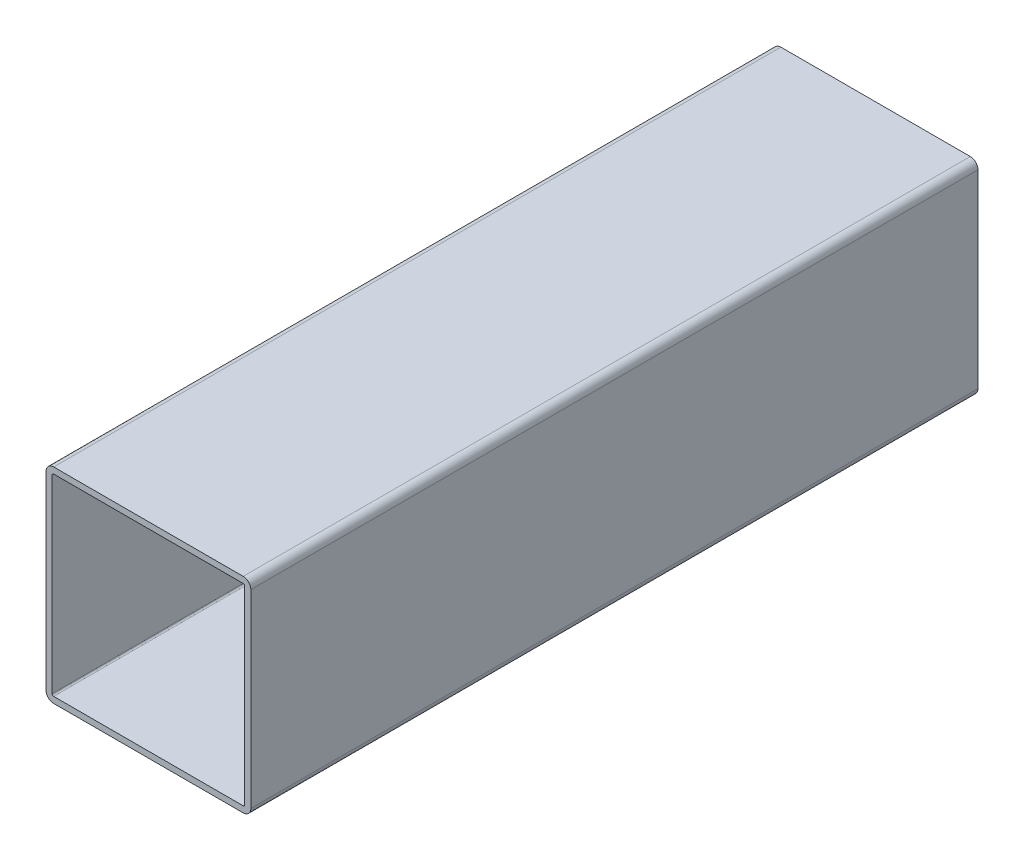
SolidWorks part; units mm, degrees
material "AISI 1020 Steel, Cold Rolled"
ref_plane "Front Plane" through (0, 0, 0) normal (0, 0, 1) x (1, 0, 0)
ref_plane "Top Plane" through (0, 0, 0) normal (0, 1, 0) x (1, 0, 0)
ref_plane "Right Plane" through (0, 0, 0) normal (1, 0, 0) x (0, 0, -1)
sketch "Sketch1" plane through (0, 0, 0) normal (0, 1, 0) x (1, 0, 0)
  line L0 (0, 0) -> (0, 142)
  dimension "D1" = 142
other "Structural Member1"
ref_plane "Plane1" through (0, 0, 0) normal (0, 0, -1) x (-1, 0, 0)
sketch "Sketch12" plane through (0, 0, 0) normal (0, 0, -1) x (-1, 0, 0)
  line L0 (-18.5, -18.8) -> (18.5, -18.8)
  line L1 (-18.8, -18.5) -> (-18.8, 18.5)
  line L2 (18.5, 18.8) -> (-18.5, 18.8)
  line L3 (18.8, 18.5) -> (18.8, -18.5)
  line L4 (-18.5, -20) -> (18.5, -20)
  line L5 (-20, -18.5) -> (-20, 18.5)
  line L6 (18.5, 20) -> (-18.5, 20)
  line L7 (20, 18.5) -> (20, -18.5)
  arc A0 (20, 18.5) -> (18.5, 20) centre (18.5, 18.5) ccw
  arc A1 (18.5, -20) -> (20, -18.5) centre (18.5, -18.5) ccw
  arc A2 (-20, -18.5) -> (-18.5, -20) centre (-18.5, -18.5) ccw
  arc A3 (-18.5, 20) -> (-20, 18.5) centre (-18.5, 18.5) ccw
  arc A4 (-18.5, 18.8) -> (-18.8, 18.5) centre (-18.5, 18.5) ccw
  arc A5 (18.8, 18.5) -> (18.5, 18.8) centre (18.5, 18.5) ccw
  arc A6 (18.5, -18.8) -> (18.8, -18.5) centre (18.5, -18.5) ccw
  arc A7 (-18.8, -18.5) -> (-18.5, -18.8) centre (-18.5, -18.5) ccw
  point P0 (-20, 0)
  point P1 (20, 0)
  point P2 (0, 20)
  point P3 (0, -20)
  point P4 (0, 0)
  point P5 (-20, -20)
  point P6 (20, -20)
  point P7 (20, 20)
  point P8 (-20, 20)
  point P33 (0, 0)
  dimension "D1" = 1.5
  dimension "Thickness" = 1.2
  dimension "V_leg" = 40
